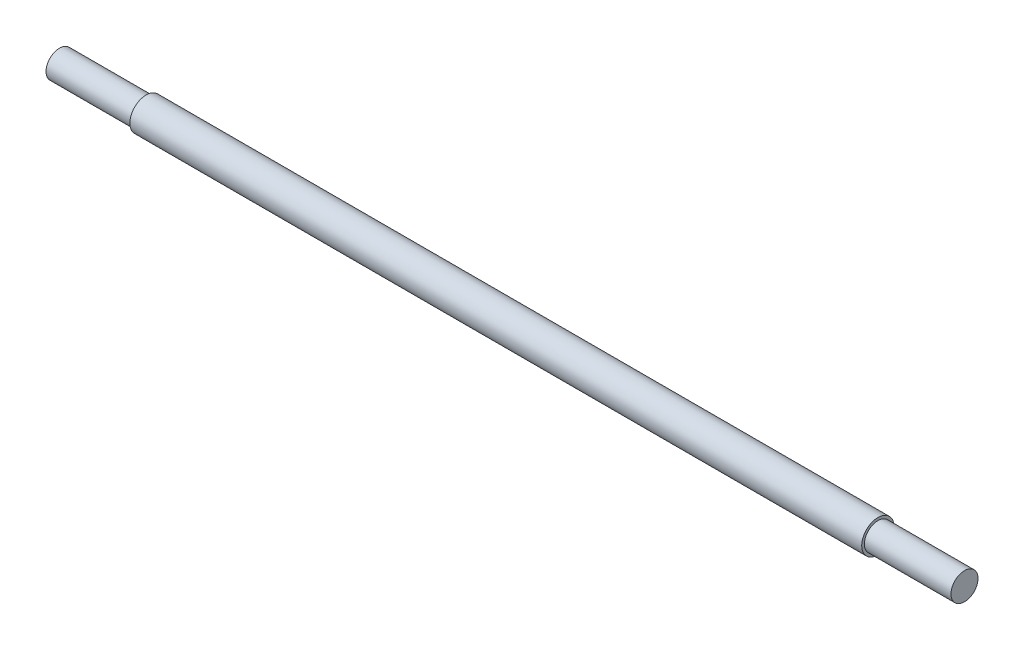
SolidWorks part; units mm, degrees
ref_plane "Front Plane" through (0, 0, 0) normal (0, 0, 1) x (1, 0, 0)
ref_plane "Top Plane" through (0, 0, 0) normal (0, 1, 0) x (1, 0, 0)
ref_plane "Right Plane" through (0, 0, 0) normal (1, 0, 0) x (0, 0, -1)
sketch "Sketch1" plane through (0, 0, 0) normal (0, 0, 1) x (1, 0, 0)
  line L0 (0, 0) -> (83.63, 0)
  line L1 (83.63, 0) -> (83.63, 1.25)
  line L2 (83.63, 1.25) -> (75.63, 1.25)
  line L3 (75.63, 1.25) -> (75.63, 1.5)
  line L4 (75.63, 1.5) -> (8, 1.5)
  line L5 (8, 1.5) -> (8, 1.25)
  line L6 (8, 1.25) -> (0, 1.25)
  line L7 (0, 1.25) -> (0, 0)
  dimension "D1" = 67.63
  dimension "D2" = 8
  dimension "D3" = 8
  dimension "D4" = 1.25
  dimension "D5" = 1.5
revolve "Revolve1" add sketch "Sketch1" angle 360 about L0
